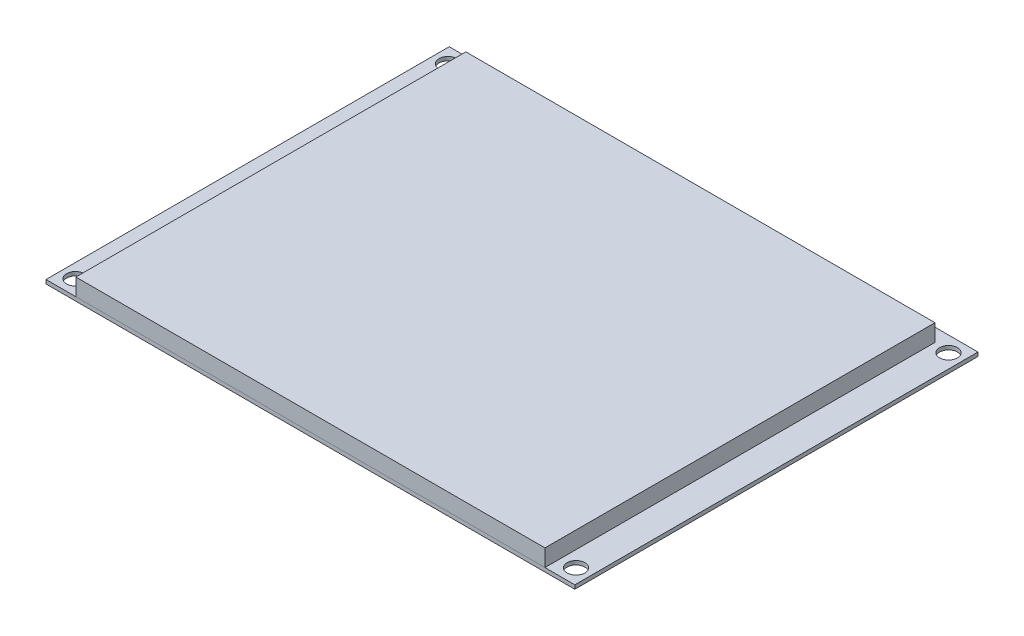
SolidWorks part; units mm, degrees
ref_plane "Front Plane" through (0, 0, 0) normal (0, 0, 1) x (1, 0, 0)
ref_plane "Top Plane" through (0, 0, 0) normal (0, 1, 0) x (1, 0, 0)
ref_plane "Right Plane" through (0, 0, 0) normal (1, 0, 0) x (0, 0, -1)
sketch "Sketch1" plane through (0, 0, 0) normal (0, 1, 0) x (1, 0, 0)
  line L1 (-43.307, 33.02) -> (43.307, 33.02)
  line L2 (-43.307, 33.02) -> (-43.307, -33.02)
  line L3 (-43.307, -33.02) -> (43.307, -33.02)
  line L4 (43.307, 33.02) -> (43.307, -33.02)
  dimension "D1" = 86.614
  dimension "D2" = 66.04
  dimension "D3" = 43.307
  dimension "D4" = 33.02
extrude "Boss-Extrude1" add sketch "Sketch1" along normal blind 0.635
sketch "Sketch2" plane through (0, 0, 0) normal (0, -1, 0) x (1, 0, 0)
  line L0 (43.307, -33.02) -> (-43.307, -33.02) construction
  line L1 (-23.749, -33.02) -> (23.749, -33.02)
  line L2 (-23.749, -33.02) -> (-23.749, -28.194)
  line L3 (-23.749, -28.194) -> (23.749, -28.194)
  line L4 (23.749, -33.02) -> (23.749, -28.194)
  dimension "D1" = 47.498
  dimension "D2" = 23.749
  dimension "D3" = 4.826
extrude "Cut-Extrude1" cut sketch "Sketch2" against normal up to surface (0.635 mm away) up to face at (0, 0.635, 0)
sketch "Sketch3" plane through (0, 0.635, 0) normal (0, 1, 0) x (1, 0, 0)
  line L0 (-43.307, -33.02) -> (43.307, -33.02) construction
  line L1 (-38.4175, -33.02) -> (38.4175, -33.02)
  line L2 (-38.4175, -33.02) -> (-38.4175, 30.861)
  line L3 (-38.4175, 30.861) -> (38.4175, 30.861)
  line L4 (38.4175, -33.02) -> (38.4175, 30.861)
  dimension "D1" = 76.835
  dimension "D2" = 38.4175
  dimension "D3" = 63.881
extrude "Boss-Extrude2" add sketch "Sketch3" along normal blind 2.794 separate body
sketch "Sketch4" plane through (0, 0, 0) normal (0, -1, 0) x (1, 0, 0)
  line L0 (-43.307, 33.02) -> (43.307, 33.02) construction
  line L1 (-13.843, -7.493) -> (13.843, -7.493)
  line L2 (-13.843, -7.493) -> (-13.843, -11.938)
  line L3 (-13.843, -11.938) -> (13.843, -11.938)
  line L4 (13.843, -7.493) -> (13.843, -11.938)
  dimension "D1" = 4.445
  dimension "D2" = 27.686
  dimension "D3" = 13.843
  dimension "D4" = 40.513
extrude "Boss-Extrude3" add sketch "Sketch4" along normal blind 2.159 separate body
sketch "Sketch6" plane through (0, 3.429, 0) normal (0, 1, 0) x (1, 0, 0)
  line L0 (-43.307, 33.02) -> (-43.307, -33.02) construction
  line L1 (-23.749, 33.02) -> (-43.307, 33.02) construction
  line L6 (43.307, 33.02) -> (23.749, 33.02) construction
  line L7 (43.307, -33.02) -> (43.307, 33.02) construction
  line L8 (-43.307, -33.02) -> (43.307, -33.02) construction
  line L9 (-43.307, -33.02) -> (43.307, -33.02) construction
  circle A0 centre (-40.9956, 30.5054) radius 1.4605
  circle A1 centre (-40.9956, -30.5054) radius 1.4605
  circle A2 centre (40.9956, -30.5054) radius 1.4605
  circle A3 centre (40.9956, 30.5054) radius 1.4605
  dimension "D1" = 2.921
  dimension "D2" = 2.921
  dimension "D3" = 2.921
  dimension "D4" = 2.921
  dimension "D5" = 2.3114
  dimension "D6" = 2.5146
  dimension "D7" = 2.5146
  dimension "D8" = 2.3114
  dimension "D9" = 2.3114
  dimension "D10" = 2.5146
  dimension "D11" = 2.3114
  dimension "D12" = 2.5146
extrude "Cut-Extrude2" cut sketch "Sketch6" against normal through all
equation "\"D3@Sketch1\"=.5*\"D1@Sketch1\""
equation "\"D4@Sketch1\"=.5*\"D2@Sketch1\""
equation "\"D2@Sketch2\"=\"D1@Sketch2\"/2"
equation "\"D2@Sketch3\"=\"D1@Sketch3\"/2"
equation "\"D3@Sketch4\"=\"D2@Sketch4\"/2"
equation "\"D2@Sketch6\"=\"D1@Sketch6\""
equation "\"D3@Sketch6\"=\"D1@Sketch6\""
equation "\"D4@Sketch6\"=\"D1@Sketch6\""
equation "\"D8@Sketch6\"=\"D5@Sketch6\""
equation "\"D7@Sketch6\"=\"D6@Sketch6\""
equation "\"D9@Sketch6\"=\"D5@Sketch6\""
equation "\"D10@Sketch6\"=\"D6@Sketch6\""
equation "\"D11@Sketch6\"=\"D5@Sketch6\""
equation "\"D12@Sketch6\"=\"D6@Sketch6\""
